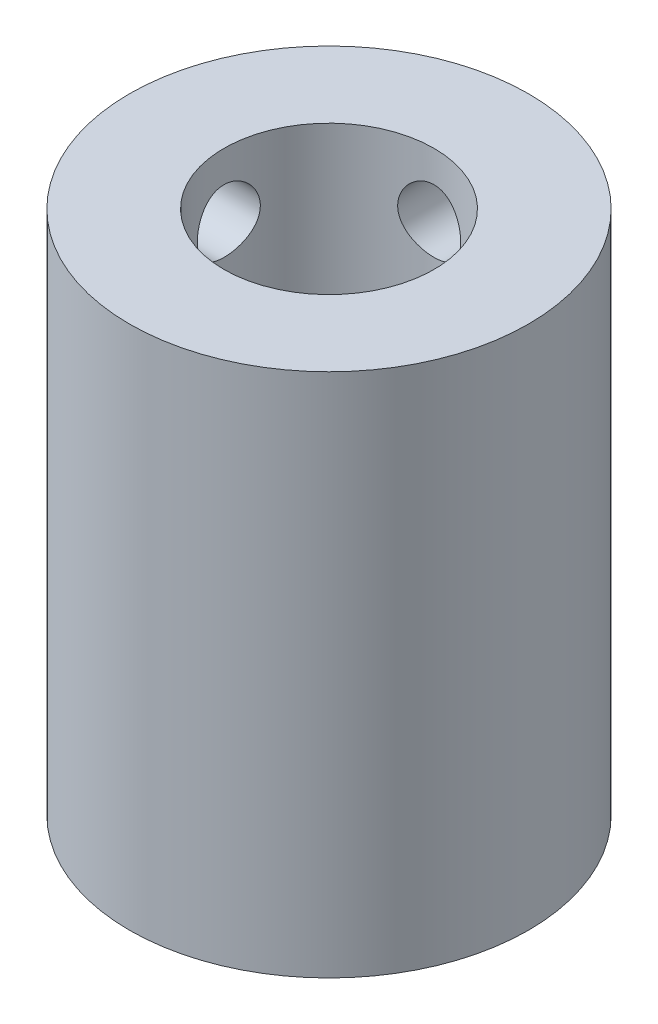
SolidWorks part; units mm, degrees
ref_plane "前视基准面" through (0, 0, 0) normal (0, 0, 1) x (1, 0, 0)
ref_plane "上视基准面" through (0, 0, 0) normal (0, 1, 0) x (1, 0, 0)
ref_plane "右视基准面" through (0, 0, 0) normal (1, 0, 0) x (0, 0, -1)
sketch "草图1" plane through (0, 0, 0) normal (0, 1, 0) x (1, 0, 0)
  circle A0 centre (0, 0) radius 9.5
  circle A1 centre (0, 0) radius 3
  dimension "D1" = 19
  dimension "D2" = 6
extrude "凸台-拉伸1" add sketch "草图1" along normal blind 25
sketch "草图2" plane through (0, 25, 0) normal (0, 1, 0) x (1, 0, 0)
  circle A0 centre (0, 0) radius 5
  dimension "D1" = 10
extrude "切除-拉伸1" cut sketch "草图2" against normal blind 10
sketch "草图3" plane through (0, 0, 0) normal (1, 0, 0) x (0, 0, -1)
  line L0 (0, 33.6391) -> (0, -8.8097) construction
  line L1 (9.5, 25) -> (-9.5, 25) construction
  circle A0 centre (0, 3) radius 1.5
  circle A1 centre (0, 22) radius 1.5
  dimension "D1" = 3
  dimension "D4" = 3
  dimension "D2" = 3
  dimension "D3" = 3
extrude "切除-拉伸2" cut sketch "草图3" against normal blind 10
sketch "草图4" plane through (0, 0, 0) normal (0, 0, 1) x (1, 0, 0)
  line L0 (0, 39.814) -> (0, -14.3868) construction
  line L2 (9.5, 25) -> (-9.5, 25) construction
  line L3 (-9.5, 0) -> (9.5, 0) construction
  circle A0 centre (0, 3) radius 1.5
  circle A1 centre (0, 22) radius 1.5
  dimension "D3" = 3
  dimension "D4" = 3
  dimension "D1" = 3
  dimension "D2" = 3
extrude "切除-拉伸3" cut sketch "草图4" against normal blind 10
